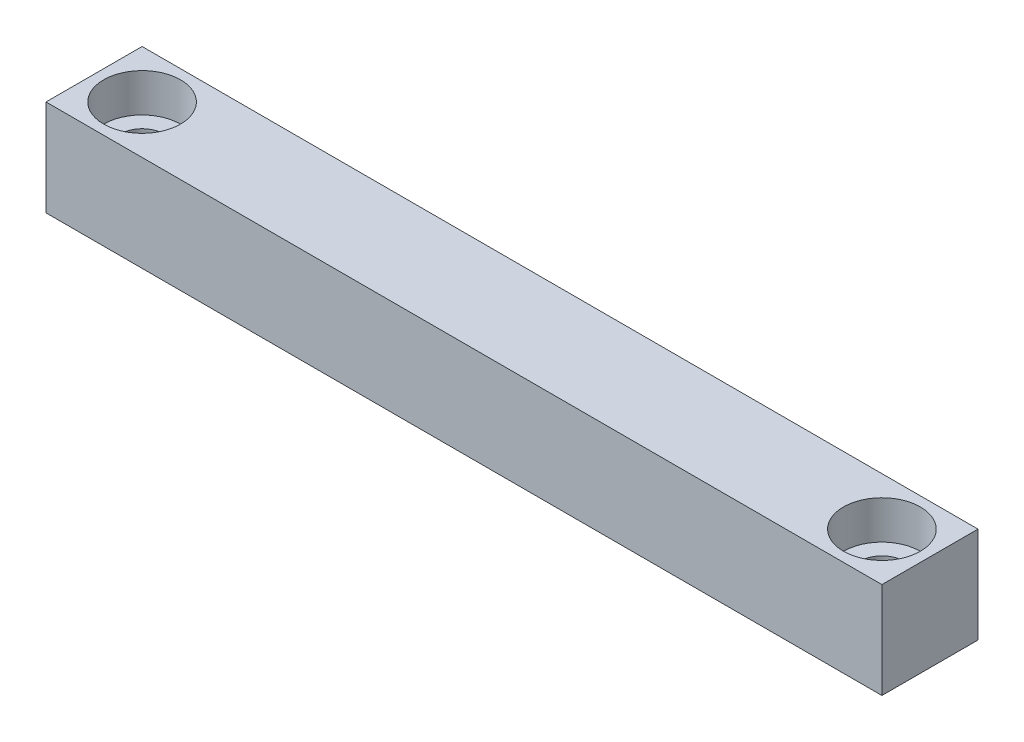
SolidWorks part; units mm, degrees
ref_plane "Front Plane" through (0, 0, 0) normal (0, 0, 1) x (1, 0, 0)
ref_plane "Top Plane" through (0, 0, 0) normal (0, 1, 0) x (1, 0, 0)
ref_plane "Right Plane" through (0, 0, 0) normal (1, 0, 0) x (0, 0, -1)
sketch "Sketch1" plane through (0, 0, 0) normal (0, 1, 0) x (1, 0, 0)
  line L1 (-43.5, -5) -> (43.5, -5)
  line L2 (-43.5, -5) -> (-43.5, 5)
  line L3 (-43.5, 5) -> (43.5, 5)
  line L4 (43.5, -5) -> (43.5, 5)
  line L5 (-43.5, -5) -> (43.5, 5) construction
  line L6 (-43.5, 5) -> (43.5, -5) construction
  point P0 (0, 0)
  dimension "D1" = 10
  dimension "D2" = 87
extrude "Boss-Extrude1" add sketch "Sketch1" along normal blind 10
sketch "Sketch2" plane through (43.5, 0, 0) normal (1, 0, 0) x (0, 0, -1)
  line L0 (0, 0) -> (0, 10) construction
  line L1 (-5, 0) -> (5, 0) construction
  line L2 (-5, 10) -> (5, 10) construction
  line L3 (0, 10) -> (-5, 5) construction
  line L4 (-5, 10) -> (-5, 0) construction
  line L5 (-5, 5) -> (5, 5) construction
  line L6 (5, 10) -> (5, 0) construction
  circle A0 centre (0, 5) radius 2.5
  dimension "D1" = 5
extrude "Cut-Extrude1" [suppressed] cut sketch "Sketch2" against normal blind 4 contours A0
mirror "Mirror1" [suppressed] about plane through (0, 0, 0) normal (1, 0, 0)
sketch "Sketch3" plane through (0, 10, 0) normal (0, 1, 0) x (1, 0, 0)
  line L0 (-43.5, 0) -> (43.5, 0) construction
  line L1 (-43.5, 5) -> (-43.5, -5) construction
  line L2 (43.5, -5) -> (43.5, 5) construction
  line L3 (43.5, 0) -> (0, 5) construction
  line L4 (43.5, 5) -> (-43.5, 5) construction
  line L5 (0, 5) -> (0, -5) construction
  line L6 (-43.5, -5) -> (43.5, -5) construction
  line L7 (-43.5, 0) -> (-41, 0) construction
  circle A0 centre (-38.5, 0) radius 2.5 construction
  point P6 (-38.5, 0)
  dimension "D1" = 2.5
hole_wizard "CBORE for M4 SHCS2" positions "Sketch3" profile "Sketch5" counterbore size "M4" standard "ANSI Metric" end condition through all
sketch "Sketch5" plane through (-38.5, 10, 0) normal (1, 0, 0) x (0, 0, 1)
  line L0 (0, 0) -> (0, 10)
  line L1 (0, 10) -> (2.25, 10)
  line L3 (2.25, 10) -> (2.25, 4)
  line L4 (2.25, 4) -> (4, 4)
  line L5 (4, 4) -> (4, 0)
  line L7 (4, 0) -> (0, 0)
  line L11 (0, -6.35) -> (0, 107.95) construction
  dimension "Thru Hole Dia." = 4.5
  dimension "Thru Hole Depth" = 10
  dimension "C'Bore Dia." = 8
  dimension "C'Bore Depth" = 4
mirror "Mirror3" about plane through (0, 0, 0) normal (1, 0, 0) of "CBORE for M4 SHCS2"
